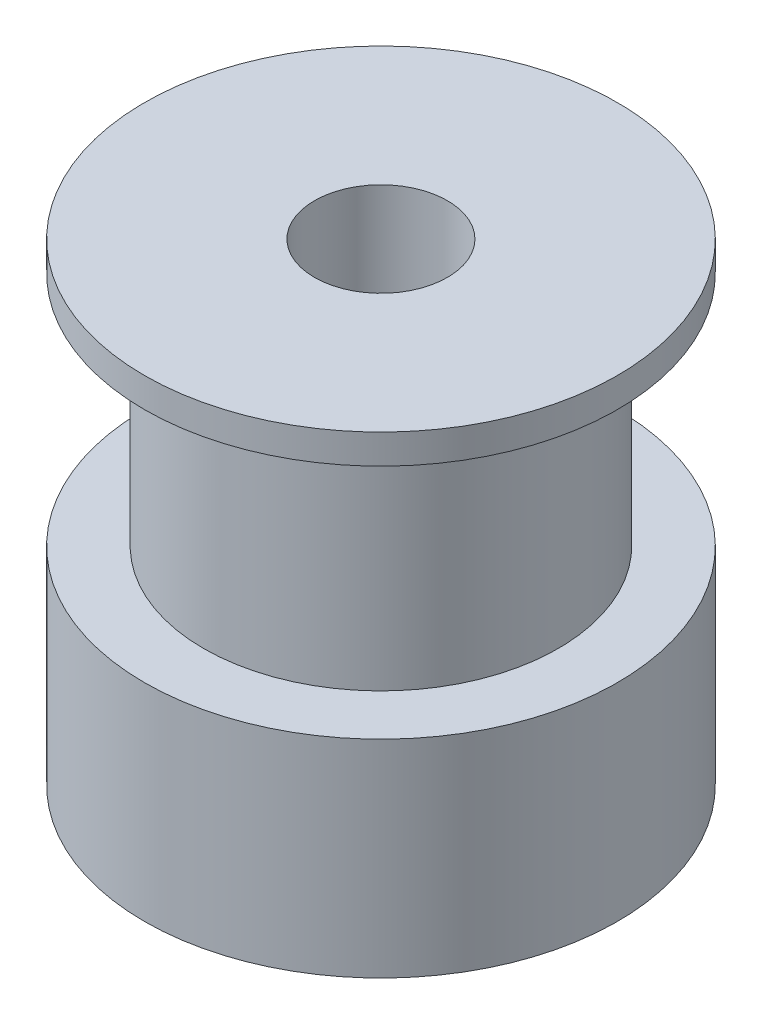
SolidWorks part; units mm, degrees
material "1060 Alloy"
ref_plane "Спереди" through (0, 0, 0) normal (0, 0, 1) x (1, 0, 0)
ref_plane "Сверху" through (0, 0, 0) normal (0, 1, 0) x (1, 0, 0)
ref_plane "Справа" through (0, 0, 0) normal (1, 0, 0) x (0, 0, -1)
sketch "Sketch1" plane through (0, 0, 0) normal (0, 1, 0) x (1, 0, 0)
  circle A0 centre (0, 0) radius 8
  dimension "D1" = 16
extrude "Boss-Extrude1" add sketch "Sketch1" along normal blind 7
sketch "Sketch2" plane through (0, 7, 0) normal (0, 1, 0) x (1, 0, 0)
  circle A0 centre (0, 0) radius 6
  dimension "D1" = 12
extrude "Boss-Extrude2" add sketch "Sketch2" along normal blind 8
sketch "Sketch3" plane through (0, 15, 0) normal (0, 1, 0) x (1, 0, 0)
  circle A0 centre (0, 0) radius 8
  dimension "D1" = 16
extrude "Boss-Extrude3" add sketch "Sketch3" along normal blind 1
sketch "Sketch4" plane through (0, 16, 0) normal (0, 1, 0) x (1, 0, 0)
  circle A0 centre (0, 0) radius 2.25
  dimension "D1" = 4.5
extrude "Cut-Extrude1" cut sketch "Sketch4" against normal up to next
